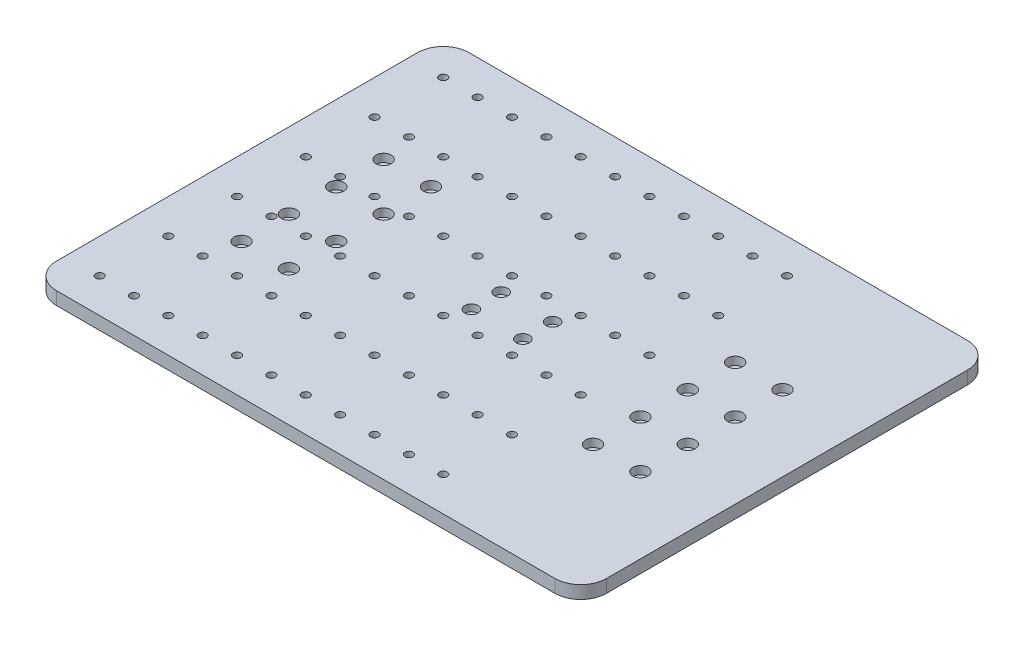
SolidWorks part; units mm, degrees
ref_plane "Front Plane" through (0, 0, 0) normal (0, 0, 1) x (1, 0, 0)
ref_plane "Top Plane" through (0, 0, 0) normal (0, 1, 0) x (1, 0, 0)
ref_plane "Right Plane" through (0, 0, 0) normal (1, 0, 0) x (0, 0, -1)
ref_plane "Plane1"
sketch "Sketch1" plane through (0, 0, 0) normal (0, 1, 0) x (-1, 0, 0)
  line L0 (203.2, 152.4) -> (-203.2, 152.4)
  line L1 (-203.2, 152.4) -> (-203.2, -152.4)
  line L2 (-203.2, -152.4) -> (203.2, -152.4)
  line L3 (203.2, -152.4) -> (203.2, 152.4)
  dimension "D1" = 406.4
  dimension "D2" = 304.8
extrude "Extrusion1" add sketch "Sketch1" along normal blind 9.525
fillet "Fillet1" radius 19.05 1 edges at (203.2, 4.7625, 152.4)
fillet "Fillet2" radius 19.05 1 edges at (203.2, 4.7625, -152.4)
fillet "Fillet3" radius 19.05 1 edges at (-203.2, 4.7625, 152.4)
fillet "Fillet4" radius 19.05 1 edges at (-203.2, 4.7625, -152.4)
hole_wizard "Hole1" positions "Sketch3" profile "Sketch2" legacy
sketch "Sketch3" plane through (0, 9.525, 0) normal (0, 1, 0) x (1, 0, 0)
  point P1 (-177.8, -127)
  point P2 (-177.8, -76.2)
  point P3 (-177.8, -25.4)
  point P4 (-177.8, 25.4)
  point P5 (-177.8, 76.2)
  point P6 (-177.8, 127)
  point P7 (-152.4, -127)
  point P8 (-152.4, -76.2)
  point P9 (-152.4, -25.4)
  point P10 (-152.4, 25.4)
  point P11 (-152.4, 76.2)
  point P12 (-152.4, 127)
  point P13 (-127, -127)
  point P14 (-127, -76.2)
  point P15 (-127, -25.4)
  point P16 (-127, 25.4)
  point P17 (-127, 76.2)
  point P18 (-127, 127)
  point P19 (-101.6, -127)
  point P20 (-101.6, -76.2)
  point P21 (-101.6, -25.4)
  point P22 (-101.6, 25.4)
  point P23 (-101.6, 76.2)
  point P24 (-101.6, 127)
  point P25 (-76.2, -127)
  point P26 (-76.2, -76.2)
  point P27 (-76.2, -25.4)
  point P28 (-76.2, 25.4)
  point P29 (-76.2, 76.2)
  point P30 (-76.2, 127)
  point P31 (-50.8, -127)
  point P32 (-50.8, -76.2)
  point P33 (-50.8, -25.4)
  point P34 (-50.8, 25.4)
  point P35 (-50.8, 76.2)
  point P36 (-50.8, 127)
  point P37 (-25.4, -127)
  point P38 (-25.4, -76.2)
  point P39 (-25.4, -25.4)
  point P40 (-25.4, 25.4)
  point P41 (-25.4, 76.2)
  point P42 (-25.4, 127)
  point P43 (0, -127)
  point P44 (0, -76.2)
  point P45 (0, -25.4)
  point P46 (0, 25.4)
  point P47 (0, 76.2)
  point P48 (0, 127)
  point P49 (25.4, -127)
  point P50 (25.4, -76.2)
  point P51 (25.4, -25.4)
  point P52 (25.4, 25.4)
  point P53 (25.4, 76.2)
  point P54 (25.4, 127)
  point P55 (50.8, -127)
  point P56 (50.8, -76.2)
  point P57 (50.8, -25.4)
  point P58 (50.8, 25.4)
  point P59 (50.8, 76.2)
  point P60 (50.8, 127)
  point P61 (76.2, -127)
  point P62 (76.2, -76.2)
  point P63 (76.2, -25.4)
  point P64 (76.2, 25.4)
  point P65 (76.2, 76.2)
  point P66 (76.2, 127)
sketch "Sketch2" plane through (-177.8, 9.525, 127) normal (1, 0, 0) x (0, 0, 1)
  line L0 (0, 0) -> (0, 27.1551)
  line L1 (0, 27.1551) -> (2.921, 25.4)
  line L2 (2.921, 25.4) -> (2.921, 0)
  line L4 (2.921, 0) -> (0, 0)
  line L6 (0, 27.1551) -> (-2.921, 25.4) construction
  line L7 (0, -4.2442) -> (0, 117.3081) construction
  dimension "Diameter" = 5.842
  dimension "Depth" = 25.4
  dimension "Drill Angle" = 118
hole_wizard "Hole4" positions "Sketch5" profile "Sketch4" legacy
sketch "Sketch5" plane through (0, 9.525, 0) normal (0, 1, 0) x (1, 0, 0)
  point P1 (-147.4, 17.5)
  point P2 (-147.4, 52.5)
  point P3 (-112.4, 52.5)
  point P4 (-112.4, -17.5)
  point P5 (-112.4, 17.5)
  point P6 (-147.4, -17.5)
  point P7 (-147.4, -52.5)
  point P8 (-112.4, -52.5)
  point P9 (112.4, -17.5)
  point P10 (147.4, -17.5)
  point P11 (147.4, -52.5)
  point P12 (112.4, -52.5)
  point P13 (112.4, 52.5)
  point P14 (147.4, 17.5)
  point P15 (112.4, 17.5)
  point P16 (147.4, 52.5)
sketch "Sketch4" plane through (-147.4, 9.525, -17.5) normal (1, 0, 0) x (0, 0, 1)
  line L0 (0, 0) -> (0, 26.9022)
  line L1 (0, 26.9022) -> (2.5, 25.4)
  line L2 (2.5, 25.4) -> (2.5, 0)
  line L4 (2.5, 0) -> (0, 0)
  line L6 (0, 26.9022) -> (-2.5, 25.4) construction
  line L7 (0, -4.2442) -> (0, 117.3081) construction
  dimension "Diameter" = 5
  dimension "Depth" = 25.4
  dimension "Drill Angle" = 118
hole_wizard "Hole5" positions "Sketch7" profile "Sketch6" legacy
sketch "Sketch7" plane through (0, 9.525, 0) normal (0, 1, 0) x (1, 0, 0)
  point P1 (-19, 11)
  point P2 (19, 11)
  point P3 (-19, -11)
  point P4 (19, -11)
sketch "Sketch6" plane through (-19, 9.525, -11) normal (1, 0, 0) x (0, 0, 1)
  line L0 (0, 0) -> (0, 26.6017)
  line L1 (0, 26.6017) -> (2, 25.4)
  line L2 (2, 25.4) -> (2, 0)
  line L4 (2, 0) -> (0, 0)
  line L6 (0, 26.6017) -> (-2, 25.4) construction
  line L7 (0, -4.2442) -> (0, 117.3081) construction
  dimension "Diameter" = 4
  dimension "Depth" = 25.4
  dimension "Drill Angle" = 118
ref_plane "Plane2" through (-147.4, 9.525, -52.5) normal (0, 1, 0) x (0, 0, -1)
hole_wizard "Hole6" positions "Sketch9" profile "Sketch8" legacy
sketch "Sketch9" plane through (-147.4, 9.525, -52.5) normal (0, 1, 0) x (0, 0, -1)
  point P1 (0, 0)
  point P2 (0, -35)
  point P3 (-35, -35)
  point P4 (-35, 0)
  point P5 (-70, 0)
  point P6 (-70, -35)
  point P7 (-105, -35)
  point P8 (-105, 0)
  point P9 (0, -259.8)
  point P10 (0, -294.8)
  point P11 (-35, -294.8)
  point P12 (-35, -259.8)
  point P13 (-70, -259.8)
  point P14 (-70, -294.8)
  point P15 (-105, -294.8)
  point P16 (-105, -259.8)
sketch "Sketch8" plane through (-147.4, 9.525, -52.5) normal (1, 0, 0) x (0, 0, 1)
  line L0 (0, 0) -> (0, 6)
  line L1 (0, 6) -> (5.6, 6)
  line L2 (5.6, 6) -> (5.6, 0)
  line L3 (5.6, 0) -> (0, 0)
  line L4 (0, 110) -> (0, -10) construction
  dimension "Diameter" = 11.2
  dimension "Depth" = 6
ref_plane "Plane3" through (-19, 9.525, -11) normal (0, 1, 0) x (0, 0, -1)
hole_wizard "Hole7" positions "Sketch11" profile "Sketch10" legacy
sketch "Sketch11" plane through (-19, 9.525, -11) normal (0, 1, 0) x (0, 0, -1)
  point P1 (0, 0)
  point P2 (0, -38)
  point P3 (-22, -38)
  point P4 (-22, 0)
sketch "Sketch10" plane through (-19, 9.525, -11) normal (1, 0, 0) x (0, 0, 1)
  line L0 (0, 0) -> (0, 5)
  line L1 (0, 5) -> (4.875, 5)
  line L2 (4.875, 5) -> (4.875, 0)
  line L3 (4.875, 0) -> (0, 0)
  line L4 (0, 110) -> (0, -10) construction
  dimension "Diameter" = 9.75
  dimension "Depth" = 5
